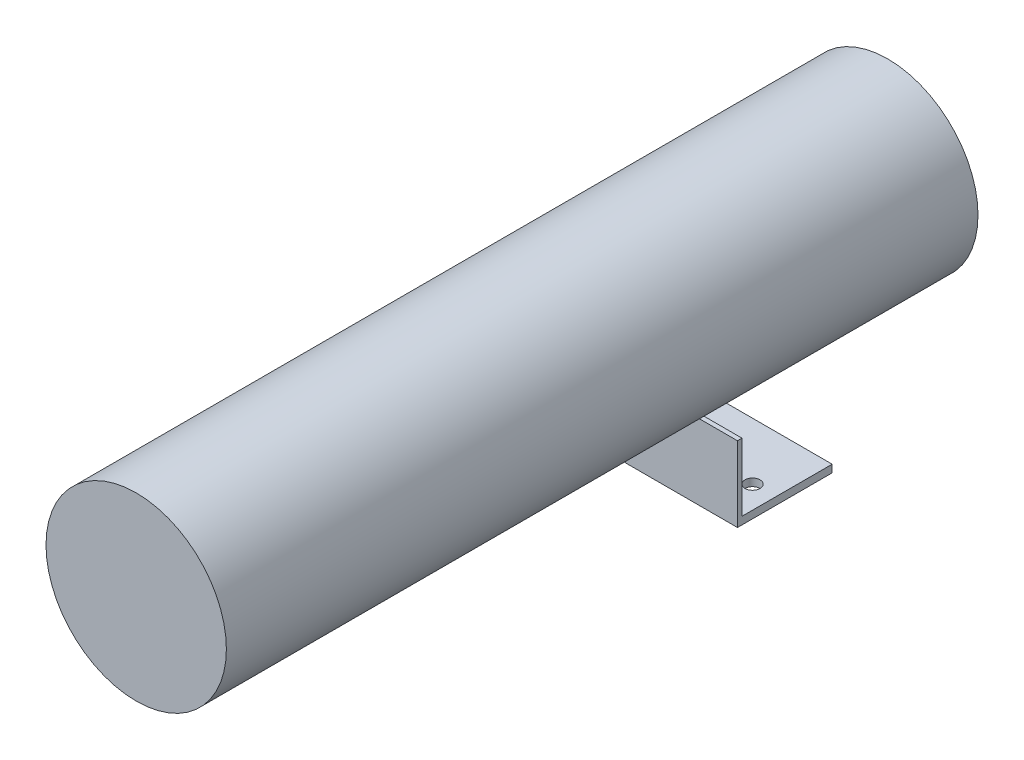
SolidWorks part; units mm, degrees
ref_plane "Front Plane" through (0, 0, 0) normal (0, 0, 1) x (1, 0, 0)
ref_plane "Top Plane" through (0, 0, 0) normal (0, 1, 0) x (1, 0, 0)
ref_plane "Right Plane" through (0, 0, 0) normal (1, 0, 0) x (0, 0, -1)
sketch "Sketch1" plane through (0, 0, 0) normal (0, 0, 1) x (1, 0, 0)
  circle A0 centre (0, 0) radius 76.2
  dimension "D1" = 152.4
extrude "Boss-Extrude2" add sketch "Sketch1" along normal blind 635
ref_plane "Plane1" through (0, 0, 0) normal (0, 0, -1) x (-1, 0, 0)
sketch "Sketch8" plane through (0, 0, 0) normal (0, 0, -1) x (-1, 0, 0)
  circle A0 centre (0, 0) radius 12.7
  dimension "D2" = 25.4
extrude "Boss-Extrude3" add sketch "Sketch8" along normal blind 12.7 separate body
sketch "Sketch9" plane through (0, 0, -12.7) normal (0, 0, -1) x (1, 0, 0)
  circle A0 centre (0, 0) radius 7.62
  dimension "D1" = 15.24
extrude "Boss-Extrude4" add sketch "Sketch9" along normal blind 5.08
sketch "Sketch10" plane through (0, 0, -17.78) normal (0, 0, -1) x (1, 0, 0)
  line L1 (0.1002, 13.0201) -> (-11.2256, 6.5968)
  line L2 (-11.2256, 6.5968) -> (-11.3258, -6.4233)
  line L3 (-11.3258, -6.4233) -> (-0.1002, -13.0201)
  line L4 (-0.1002, -13.0201) -> (11.2256, -6.5968)
  line L5 (11.2256, -6.5968) -> (11.3258, 6.4233)
  line L6 (11.3258, 6.4233) -> (0.1002, 13.0201)
  circle A0 centre (0, 0) radius 11.2761 construction
  dimension "D1" = 22.5521
extrude "Boss-Extrude5" add sketch "Sketch10" along normal blind 7.62
sketch "Sketch11" plane through (0, 0, -25.4) normal (0, 0, -1) x (1, 0, 0)
  line L0 (-11.3258, -6.4233) -> (-0.1002, -13.0201) construction
  line L1 (-7.4089, 4.3539) -> (-7.475, -4.2393)
  line L2 (-7.475, -4.2393) -> (-0.0661, -8.5932)
  line L3 (-0.0661, -8.5932) -> (7.4089, -4.3539)
  line L4 (7.4089, -4.3539) -> (7.475, 4.2393)
  line L5 (7.475, 4.2393) -> (0.0661, 8.5932)
  line L6 (0.0661, 8.5932) -> (-7.4089, 4.3539)
  circle A0 centre (0, 0) radius 7.4421 construction
  dimension "D1" = 14.8843
extrude "Boss-Extrude6" add sketch "Sketch11" along normal blind 2.54
sketch "Sketch12" plane through (0, 0, -27.94) normal (0, 0, -1) x (1, 0, 0)
  circle A0 centre (0, 0) radius 5.08
  dimension "D1" = 10.16
extrude "Boss-Extrude7" add sketch "Sketch12" along normal blind 5.08
ref_plane "Plane2" through (0, 0, 190.5) normal (0, 0, -1) x (-1, 0, 0)
sketch "Sketch14" plane through (0, 0, 190.5) normal (0, 0, -1) x (-1, 0, 0)
  line L0 (-63.5, -76.2) -> (63.5, -76.2)
  line L1 (-63.5, -76.2) -> (-63.5, -139.7)
  line L2 (-63.5, -139.7) -> (63.5, -139.7)
  line L3 (63.5, -139.7) -> (63.5, -76.2)
  circle A0 centre (0, 0) radius 76.2 construction
  dimension "D1" = 63.5
  dimension "D2" = 63.5
  dimension "D3" = 63.5
extrude "Boss-Extrude8" add sketch "Sketch14" along normal blind 3.81 separate body
sketch "Sketch15" plane through (0, 0, 186.69) normal (0, 0, -1) x (-1, 0, 0)
  line L0 (-63.5, -76.2) -> (-63.5, -139.7) construction
  line L1 (-63.5, -133.35) -> (63.5, -133.35)
  line L2 (-63.5, -133.35) -> (-63.5, -139.7)
  line L3 (-63.5, -139.7) -> (63.5, -139.7)
  line L4 (63.5, -133.35) -> (63.5, -139.7)
  dimension "D1" = 6.35
extrude "Boss-Extrude9" add sketch "Sketch15" along normal blind 76.2
sketch "Sketch16" plane through (0, -133.35, 0) normal (0, 1, 0) x (1, 0, 0)
  line L0 (63.5, -110.49) -> (63.5, -186.69) construction
  line L1 (-63.5, -110.49) -> (-63.5, -186.69) construction
  line L2 (-63.5, -186.69) -> (63.5, -186.69) construction
  circle A0 centre (44.45, -158.75) radius 6.35
  circle A1 centre (-44.45, -158.75) radius 6.35
  dimension "D1" = 12.7
  dimension "D2" = 19.05
  dimension "D3" = 19.05
  dimension "D4" = 27.94
extrude "Cut-Extrude1" cut sketch "Sketch16" against normal through all
